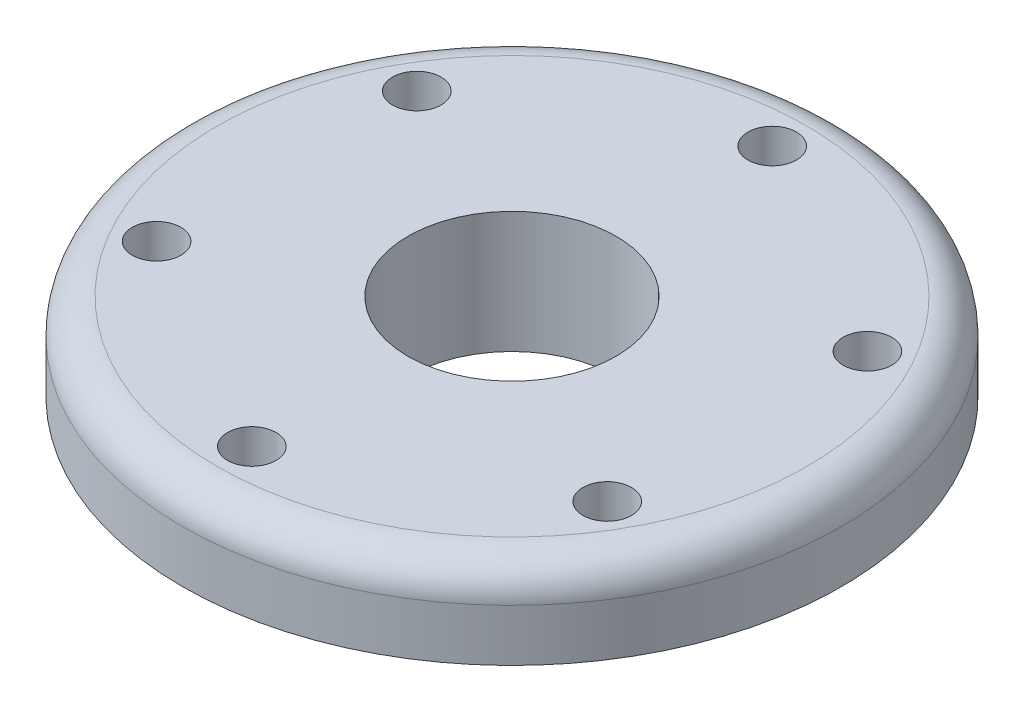
SolidWorks part; units mm, degrees
ref_plane "Front Plane" through (0, 0, 0) normal (0, 0, 1) x (1, 0, 0)
ref_plane "Top Plane" through (0, 0, 0) normal (0, 1, 0) x (1, 0, 0)
ref_plane "Right Plane" through (0, 0, 0) normal (1, 0, 0) x (0, 0, -1)
sketch "Sketch1" plane through (0, 0, 0) normal (0, 1, 0) x (1, 0, 0)
  circle A0 centre (0, 0) radius 12
  dimension "D1" = 24
extrude "Boss-Extrude1" add sketch "Sketch1" along normal blind 2
sketch "Sketch2" plane through (0, 2, 0) normal (0, 1, 0) x (1, 0, 0)
  circle A0 centre (0, 0) radius 19
  dimension "D1" = 38
extrude "Boss-Extrude2" add sketch "Sketch2" along normal blind 5
fillet "Fillet1" radius 2 1 edges at (0, 7, 19)
sketch "Sketch3" plane through (0, 7, 0) normal (0, 1, 0) x (1, 0, 0)
  circle A0 centre (0, 0) radius 6
  circle A1 centre (0, 15) radius 1.4
  circle A2 centre (12.9904, 7.5) radius 1.4
  circle A3 centre (12.9904, -7.5) radius 1.4
  circle A4 centre (0, -15) radius 1.4
  circle A5 centre (-12.9904, -7.5) radius 1.4
  circle A6 centre (-12.9904, 7.5) radius 1.4
  circle A7 centre (0, 0) radius 17 construction
  point P17 (0, 0)
  dimension "D1" = 12
  dimension "D2" = 2.8
  dimension "D3" = 15
  dimension "D4" = 6
extrude "Cut-Extrude1" cut sketch "Sketch3" against normal through all
